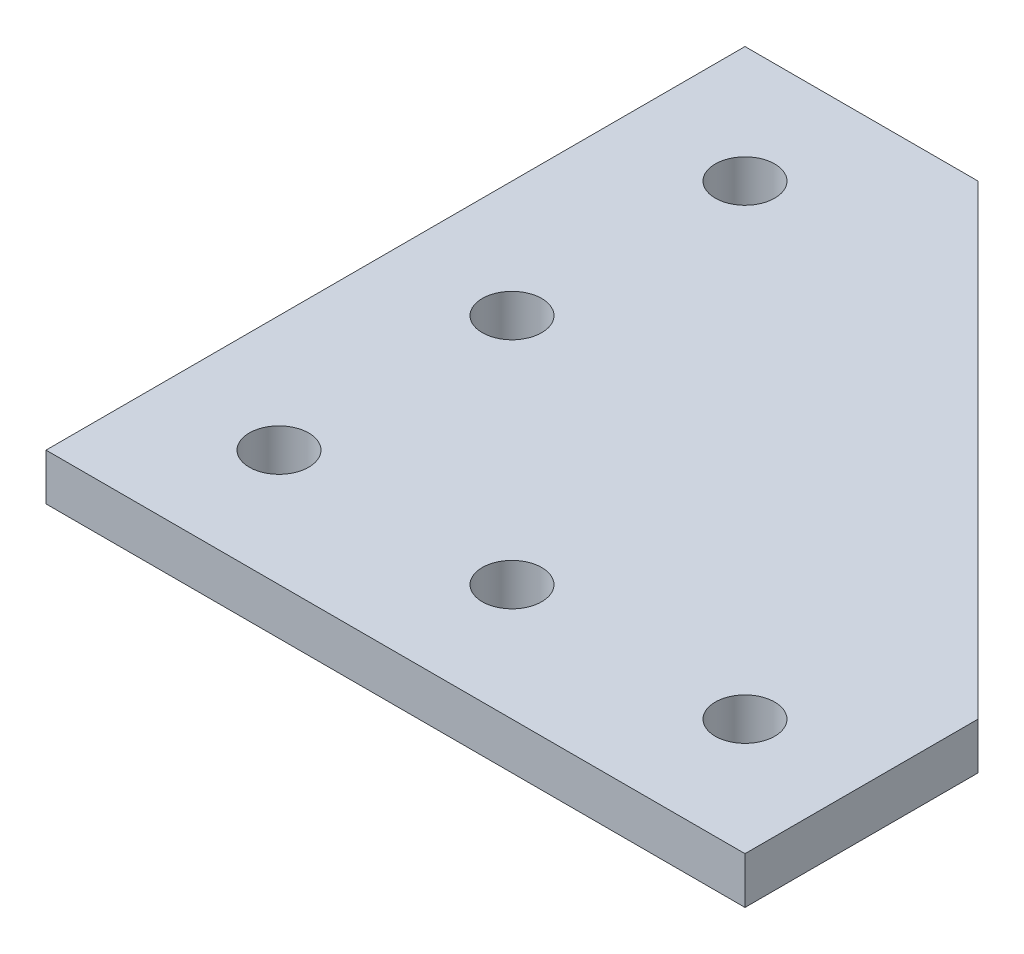
SolidWorks part; units mm, degrees
material "6061-T6 (SS)"
ref_plane "Front Plane" through (0, 0, 0) normal (0, 0, 1) x (1, 0, 0)
ref_plane "Top Plane" through (0, 0, 0) normal (0, 1, 0) x (1, 0, 0)
ref_plane "Right Plane" through (0, 0, 0) normal (1, 0, 0) x (0, 0, -1)
sketch "Sketch1" plane through (0, 0, 0) normal (0, 1, 0) x (1, 0, 0)
  line L0 (0, 0) -> (60, 0)
  line L1 (60, 0) -> (60, 20)
  line L2 (60, 20) -> (20, 60)
  line L3 (20, 60) -> (0, 60)
  line L4 (0, 60) -> (0, 0)
  circle A0 centre (10, 10) radius 2.55
  circle A1 centre (30, 10) radius 2.55
  circle A2 centre (50, 10) radius 2.55
  circle A3 centre (10, 30) radius 2.55
  circle A4 centre (10, 50) radius 2.55
  dimension "D5" = 5.1
  dimension "D1" = 60
  dimension "D2" = 60
  dimension "D3" = 20
  dimension "D4" = 20
  dimension "D6" = 10
  dimension "D7" = 10
  dimension "D8" = 30
  dimension "D9" = 50
  dimension "D10" = 30
  dimension "D11" = 50
extrude "Boss-Extrude1" add sketch "Sketch1" along normal blind 4
